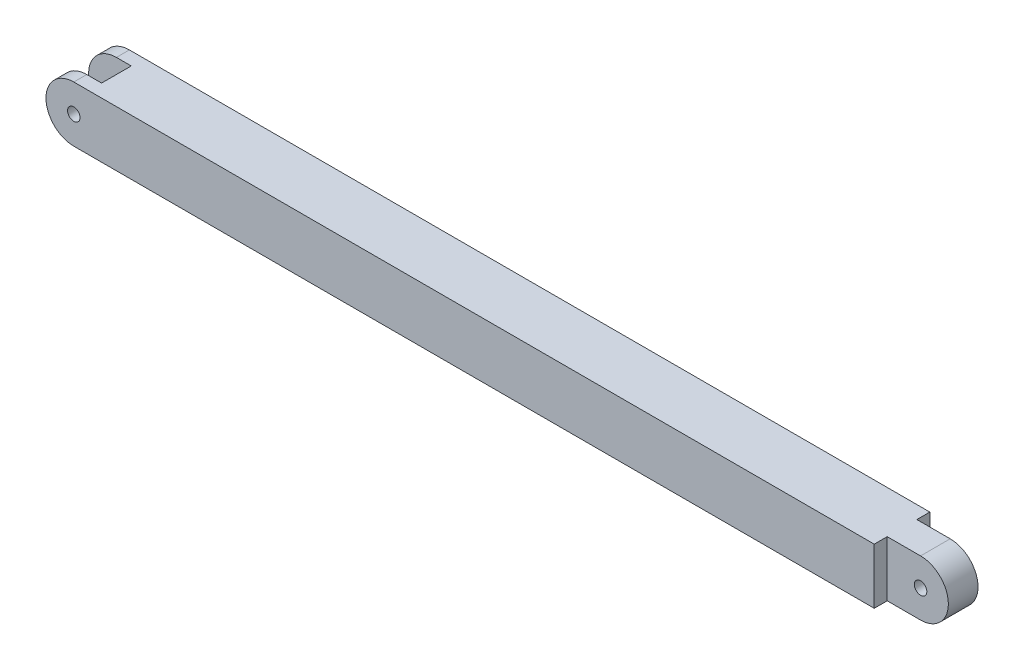
SolidWorks part; units mm, degrees
ref_plane "Front Plane" through (0, 0, 0) normal (0, 0, 1) x (1, 0, 0)
ref_plane "Top Plane" through (0, 0, 0) normal (0, 1, 0) x (1, 0, 0)
ref_plane "Right Plane" through (0, 0, 0) normal (1, 0, 0) x (0, 0, -1)
sketch "Sketch1" plane through (0, 0, 0) normal (0, 0, 1) x (1, 0, 0)
  line L0 (-225, 0) -> (225, 0) construction
  line L1 (-225, 15) -> (225, 15)
  line L2 (-225, -15) -> (225, -15)
  arc A0 (-225, 15) -> (-225, -15) centre (-225, 0) ccw
  arc A1 (225, -15) -> (225, 15) centre (225, 0) ccw
  point P2 (0, 0)
  dimension "D1" = 450
  dimension "D2" = 30
extrude "Boss-Extrude1" add sketch "Sketch1" along normal mid plane 30
hole_wizard "H (0.266) Diameter Hole1" positions "Sketch2" profile "Sketch4" hole size "H" standard "ANSI Inch" end condition through all
sketch "Sketch2" plane through (0, 0, 15) normal (0, 0, 1) x (1, 0, 0)
  point P0 (-225, 0)
  point P3 (225, 0)
sketch "Sketch4" plane through (-225, 0, 15) normal (1, 0, 0) x (0, -1, 0)
  line L0 (0, 0) -> (0, 30)
  line L1 (0, 30) -> (3.3782, 30)
  line L2 (3.3782, 30) -> (3.3782, 0)
  line L5 (3.3782, 0) -> (0, 0)
  line L11 (0, -6.35) -> (0, 107.95) construction
  dimension "Thru Hole Dia." = 6.7564
  dimension "Thru Hole Depth" = 30
sketch "Sketch5" plane through (0, 15, 0) normal (0, 1, 0) x (1, 0, 0)
  line L1 (-257, 8) -> (-217, 8)
  line L2 (-257, 8) -> (-257, -8)
  line L3 (-257, -8) -> (-217, -8)
  line L4 (-217, 8) -> (-217, -8)
  line L5 (-217, 0) -> (0, 0) construction
  line L6 (-225, -15) -> (-225, 15) construction
  line L7 (225, -15) -> (225, 15) construction
  line L8 (207, 28.9161) -> (247, 28.9161)
  line L9 (207, 28.9161) -> (207, 8)
  line L10 (207, 8) -> (247, 8)
  line L11 (247, 28.9161) -> (247, 8)
  line L12 (207, -28.9161) -> (247, -28.9161)
  line L13 (207, -28.9161) -> (207, -8)
  line L14 (207, -8) -> (247, -8)
  line L15 (247, -28.9161) -> (247, -8)
  dimension "D1" = 16
  dimension "D2" = 8
  dimension "D3" = 40
  dimension "D4" = 18
extrude "Cut-Extrude1" cut sketch "Sketch5" against normal through all
